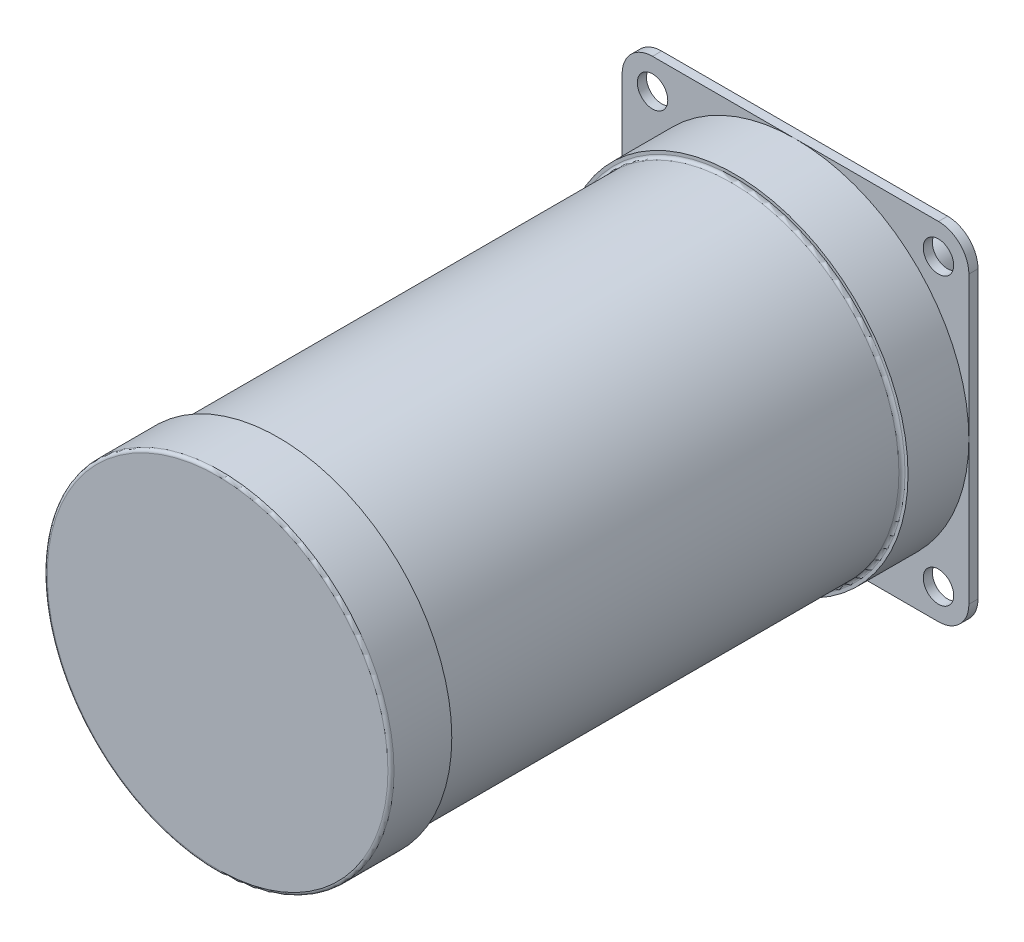
SolidWorks part; units mm, degrees
ref_plane "Front Plane" through (0, 0, 0) normal (0, 0, 1) x (1, 0, 0)
ref_plane "Top Plane" through (0, 0, 0) normal (0, 1, 0) x (1, 0, 0)
ref_plane "Right Plane" through (0, 0, 0) normal (1, 0, 0) x (0, 0, -1)
sketch "Sketch1" plane through (0, 0, 0) normal (0, 0, 1) x (1, 0, 0)
  line L0 (0, 0) -> (57, 0)
  line L1 (57, 0) -> (57, 57)
  line L2 (57, 57) -> (0, 57)
  line L3 (0, 57) -> (0, 0)
  dimension "D1" = 57
extrude "Boss-Extrude1" add sketch "Sketch1" along normal blind 1.5
sketch "Sketch2" plane through (0, 0, 1.5) normal (0, 0, 1) x (1, 0, 0)
  line L0 (57, 57) -> (0, 57) construction
  line L1 (0, 57) -> (0, 0) construction
  circle A0 centre (28.5, 28.5) radius 28.5
  point P2 (0, 0)
  point P5 (28.5, 57)
  point P8 (0, 28.5)
  dimension "D1" = 57
extrude "Boss-Extrude2" add sketch "Sketch2" along normal blind 10
sketch "Sketch3" plane through (0, 0, 11.5) normal (0, 0, 1) x (1, 0, 0)
  circle A0 centre (28.5, 28.5) radius 27.5
  dimension "D1" = 55
extrude "Boss-Extrude3" add sketch "Sketch3" along normal blind 75
sketch "Sketch4" plane through (0, 0, 86.5) normal (0, 0, 1) x (1, 0, 0)
  circle A0 centre (28.5, 28.5) radius 28.5
  dimension "D1" = 57
extrude "Boss-Extrude4" add sketch "Sketch4" along normal blind 10
sketch "Sketch5" plane through (0, 0, 0) normal (0, 0, -1) x (-1, 0, 0)
  line L0 (-57, 57) -> (0, 57) construction
  line L1 (-57, 0) -> (-57, 57) construction
  circle A0 centre (-52, 52) radius 2.5
  circle A1 centre (-5, 52) radius 2.5
  circle A2 centre (-5, 5) radius 2.5
  circle A3 centre (-52, 5) radius 2.5
  point P10 (-47.8097, 47.5589)
  point P13 (0, 0)
  point P14 (0, 0)
  point P15 (0, 0)
  point P16 (0, 0)
  point P17 (0, 0)
  point P18 (0, 0)
  dimension "D7" = 5
  dimension "D8" = 5
  dimension "D9" = 5
  dimension "D10" = 5
  dimension "D1" = 47
  dimension "D2" = 47
  dimension "D3" = 47
  dimension "D4" = 47
  dimension "D5" = 5
  dimension "D6" = 5
extrude "Cut-Extrude1" cut sketch "Sketch5" against normal up to next
sketch "Sketch6" plane through (0, 0, 0) normal (0, 0, -1) x (-1, 0, 0)
  line L0 (-57, 57) -> (0, 57) construction
  line L1 (0, 57) -> (0, 0) construction
  circle A0 centre (-28.5, 28.5) radius 19
  point P4 (-28.5, 57)
  point P5 (0, 0)
  point P8 (0, 28.5)
  dimension "D1" = 38
extrude "Boss-Extrude5" add sketch "Sketch6" along normal blind 1.5
sketch "Sketch7" plane through (0, 0, -1.5) normal (0, 0, -1) x (-1, 0, 0)
  circle A0 centre (-28.5, 28.5) radius 4
  dimension "D1" = 8
extrude "Boss-Extrude6" add sketch "Sketch7" along normal blind 20
fillet "Fillet1" radius 5 4 edges at (57, 0, 0.75) (0, 0, 0.75) (0, 57, 0.75) (57, 57, 0.75)
fillet "Fillet2" radius 0.5 5 edges at (9.5, 28.5, -1.5) (47.5, 28.5, 0) (57, 28.5, 96.5) (56, 28.5, 86.5) (56, 28.5, 11.5)
